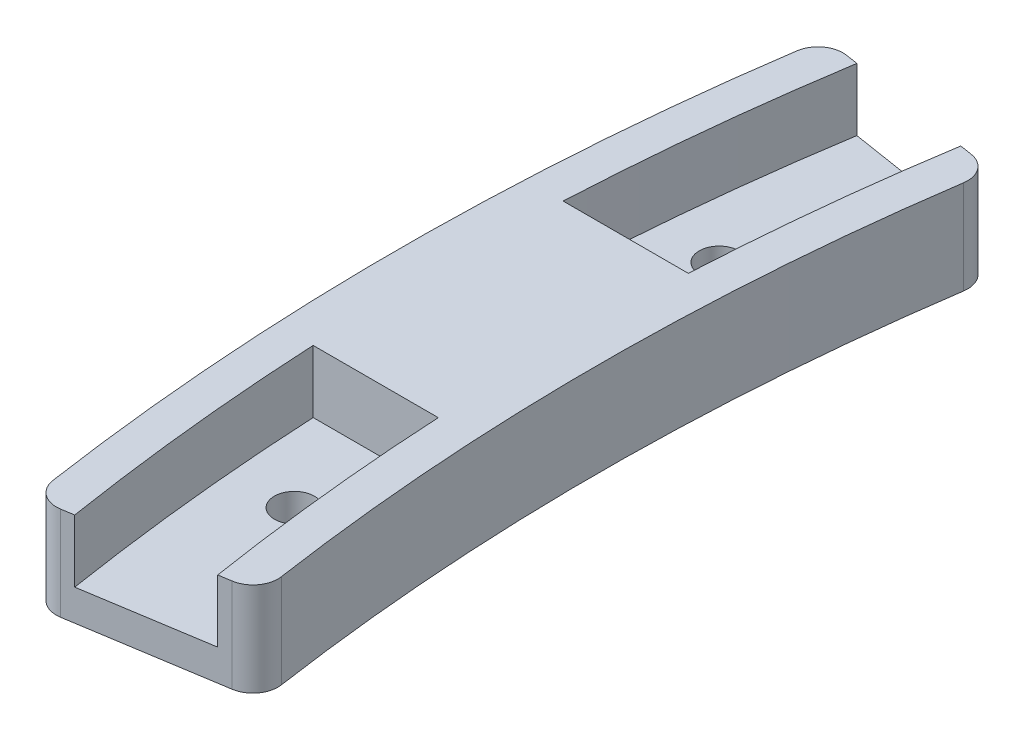
SolidWorks part; units mm, degrees
ref_plane "Front Plane" through (0, 0, 0) normal (0, 0, 1) x (1, 0, 0)
ref_plane "Top Plane" through (0, 0, 0) normal (0, 1, 0) x (1, 0, 0)
ref_plane "Right Plane" through (0, 0, 0) normal (1, 0, 0) x (0, 0, -1)
sketch "Sketch1" plane through (0, 0, 0) normal (0, 1, 0) x (1, 0, 0)
  line L0 (0, 0) -> (-197.5377, -31.2869) construction
  line L1 (0, 0) -> (-197.5377, 31.2869) construction
  line L2 (0, 0) -> (-195, 0) construction
  line L3 (-197.5377, 31.2869) -> (-187.6608, 29.7225)
  line L4 (-187.6608, -29.7225) -> (-197.5377, -31.2869)
  line L5 (0, 0) -> (-200.5007, -31.7562) construction
  line L6 (0, 0) -> (-200.5007, 31.7562) construction
  line L7 (-200.5007, 31.7562) -> (-184.6977, 29.2532)
  line L8 (-200.5007, -31.7562) -> (-184.6977, -29.2532)
  arc A0 (-197.5377, 31.2869) -> (-197.5377, -31.2869) centre (0, 0) ccw
  arc A1 (-187.6608, 29.7225) -> (-187.6608, -29.7225) centre (0, 0) ccw
  arc A2 (-192.5992, -30.5047) -> (-192.5992, 30.5047) centre (0, 0) cw construction
  arc A4 (-184.6977, 29.2532) -> (-184.6977, -29.2532) centre (0, 0) ccw
  arc A5 (-200.5007, 31.7562) -> (-200.5007, -31.7562) centre (0, 0) ccw
  dimension "D1" = 200
  dimension "D2" = 190
  dimension "D3" = 5
  dimension "D5" = 187
  dimension "D6" = 203
  dimension "D4" = 18
extrude "Boss-Extrude1" add sketch "Sketch1" along normal blind 10 contours A1 L3 A0 L4 | L7 A5 L8 A0 | A4 L7 A1 L8
ref_plane "Plane1" through (-195, 0, 0) normal (1, 0, 0) x (0, 0, -1)
sketch "Sketch15" plane through (0, 10, 0) normal (0, 1, 0) x (1, 0, 0)
  line L0 (-187.6608, -29.7225) -> (-197.5377, -31.2869) construction
  line L1 (-185, 10) -> (-205, 10)
  line L2 (-185, 10) -> (-185, -10)
  line L3 (-185, -10) -> (-205, -10)
  line L4 (-205, 10) -> (-205, -10)
  line L5 (-185, 10) -> (-205, -10) construction
  line L6 (-185, -10) -> (-205, 10) construction
  line L7 (-197.5377, 31.2869) -> (-187.6608, 29.7225) construction
  line L8 (-187.6608, -29.7225) -> (-197.5377, -31.2869)
  line L9 (-197.5377, 31.2869) -> (-187.6608, 29.7225)
  arc A2 (-187.6608, 29.7225) -> (-187.6608, -29.7225) centre (0, 0) ccw construction
  arc A3 (-197.5377, 31.2869) -> (-197.5377, -31.2869) centre (0, 0) ccw construction
  arc A4 (-187.6608, 29.7225) -> (-187.6608, -29.7225) centre (0, 0) ccw
  arc A5 (-197.5377, 31.2869) -> (-197.5377, -31.2869) centre (0, 0) ccw
  point P0 (-195, 0)
  line M5 (-200.5007, -31.7562) -> (-184.6977, -29.2532)
  line M7 (-184.6977, 29.2532) -> (-200.5007, 31.7562)
  dimension "D1" = 20
  dimension "D2" = 20
extrude "Cut-Extrude1" cut sketch "Sketch15" against normal blind 5 contours A5 L1 A4 M7 | L3 A5 A4 M5
ref_plane "Plane2" through (-195, 0, 0) normal (-1, 0, 0) x (0, 0, 1)
sketch "Sketch12" plane through (0, 0, 0) normal (0, 1, 0) x (1, 0, 0)
  line L0 (0, 0) -> (-194.258, -16.9954) construction
  line L1 (0, 0) -> (-193.3317, -25.4526) construction
  line L2 (0, 0) -> (-195, 0) construction
  line L3 (0, 0) -> (-195, 0) construction
  line L4 (0, 0) -> (-194.258, 16.9954) construction
  line L5 (0, 0) -> (-193.3317, 25.4526) construction
  arc A0 (-192.5992, 30.5047) -> (-192.5992, -30.5047) centre (0, 0) ccw construction
  dimension "D1" = 10
  dimension "D2" = 15
fillet "Fillet1" radius 2 4 edges at (-200.5007, 5, -31.7562) (-184.6977, 5, -29.2532) (-200.5007, 5, 31.7562) (-184.6977, 5, 29.2532)
sketch "Sketch19" plane through (0, 0, 0) normal (0, -1, 0) x (1, 0, 0)
  line L2 (-198.5155, -31.4418) -> (-186.6626, -29.5645)
  line L3 (-186.6626, 29.5645) -> (-198.5155, 31.4418)
  line L4 (-198.5155, -31.4418) -> (-186.6626, -29.5645)
  line L5 (-186.6626, 29.5645) -> (-198.5155, 31.4418)
  arc A6 (-200.8068, 29.7596) -> (-200.8068, -29.7596) centre (0, 0) ccw
  arc A7 (-200.8068, -29.7596) -> (-198.5155, -31.4418) centre (-198.8284, -29.4664) ccw
  arc A8 (-186.6626, -29.5645) -> (-184.9969, -27.2971) centre (-186.9755, -27.5891) ccw
  arc A9 (-184.9969, 27.2971) -> (-184.9969, -27.2971) centre (0, 0) ccw
  arc A10 (-184.9969, 27.2971) -> (-186.6626, 29.5645) centre (-186.9755, 27.5891) ccw
  arc A11 (-198.5155, 31.4418) -> (-200.8068, 29.7596) centre (-198.8284, 29.4664) ccw
  arc A12 (-200.8068, 29.7596) -> (-200.8068, -29.7596) centre (0, 0) ccw
  arc A13 (-200.8068, -29.7596) -> (-198.5155, -31.4418) centre (-198.8284, -29.4664) ccw
  arc A14 (-186.6626, -29.5645) -> (-184.9969, -27.2971) centre (-186.9755, -27.5891) ccw
  arc A15 (-184.9969, 27.2971) -> (-184.9969, -27.2971) centre (0, 0) ccw
  arc A16 (-184.9969, 27.2971) -> (-186.6626, 29.5645) centre (-186.9755, 27.5891) ccw
  arc A17 (-198.5155, 31.4418) -> (-200.8068, 29.7596) centre (-198.8284, 29.4664) ccw
  dimension "D1" = 0
extrude "Cut-Extrude2" cut sketch "Sketch19" against normal blind 2.5
hole_wizard "Ø3.2 (3.2) Diameter Hole1" positions "Sketch20" profile "Sketch21" hole size "Ø3.2" standard "ISO" end condition through all
sketch "Sketch20" plane through (0, 2.5, 0) normal (0, -1, 0) x (-1, 0, 0)
  point P0 (194.258, 16.9954)
  point P3 (194.258, -16.9954)
sketch "Sketch21" plane through (-194.258, 2.5, -16.9954) normal (1, 0, 0) x (0, 0, -1)
  line L0 (0, 0) -> (0, 7.5)
  line L1 (0, 7.5) -> (1.6, 7.5)
  line L2 (1.6, 7.5) -> (1.6, 0)
  line L5 (1.6, 0) -> (0, 0)
  line L11 (0, -6.35) -> (0, 107.95) construction
  dimension "Thru Hole Dia." = 3.2
  dimension "Thru Hole Depth" = 7.5
